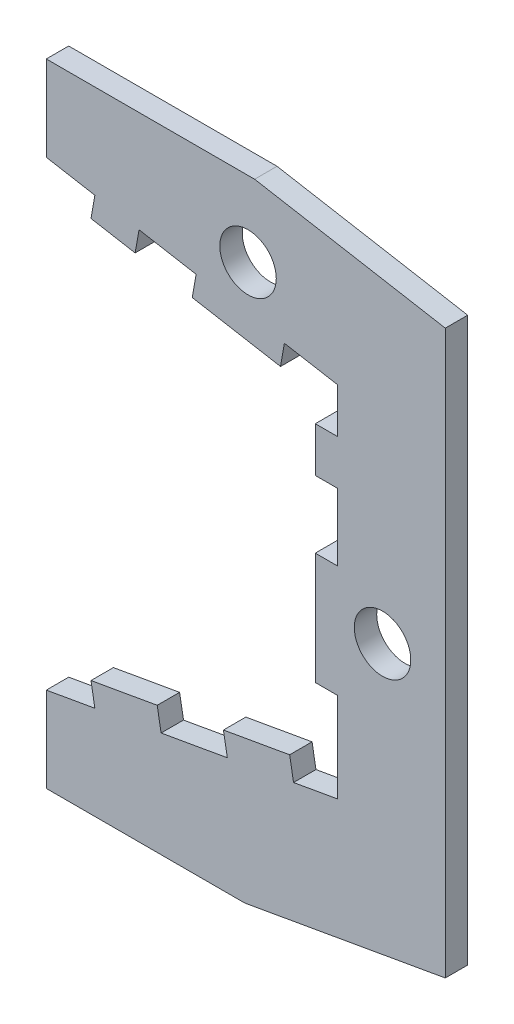
SolidWorks part; units mm, degrees
material "Balsa"
ref_plane "Plan de face" through (0, 0, 0) normal (0, 0, 1) x (1, 0, 0)
ref_plane "Plan de dessus" through (0, 0, 0) normal (0, 1, 0) x (1, 0, 0)
ref_plane "Plan de droite" through (0, 0, 0) normal (1, 0, 0) x (0, 0, -1)
sketch "Esquisse1" plane through (0, 0, 0) normal (0, 0, 1) x (1, 0, 0)
  line L0 (-65, 51.4613) -> (0, 40)
  line L1 (0, 40) -> (0, -40)
  line L2 (-65, -51.4613) -> (0, -40)
  line L3 (-18.4444, 71.4613) -> (-65, 71.4613)
  line L4 (-65, -51.4613) -> (-65, -71.4613)
  line L5 (-20.6259, -71.4613) -> (25, -63.4162)
  line L6 (25, -63.4162) -> (25, 63.8008)
  line L7 (25, 63.8008) -> (-18.4444, 71.4613)
  line L8 (-65, 71.4613) -> (-65, 51.4613)
  line L9 (-18.4444, 71.4613) -> (-20, 53.6808) construction
  line L10 (-65, -71.4613) -> (-20.6259, -71.4613)
  line L11 (0, 0) -> (-84.8855, 0) construction
  circle A0 centre (-20, 53.6808) radius 6.3
  circle A1 centre (10, -5) radius 6.3
  point P4 (-30.4766, 71.4613)
  point P13 (-6.595, 69.3719)
  point P15 (-65, -71.4613)
  dimension "D1" = 12.6
  dimension "D13" = 12.6
  dimension "D2" = 10
  dimension "D3" = 20
  dimension "D4" = 80
  dimension "D5" = 65
  dimension "D6" = 100
  dimension "D7" = 100
  dimension "D8" = 20
  dimension "D9" = 27.4016
  dimension "D10" = 90
  dimension "D11" = 10
  dimension "D12" = 35
  dimension "D14" = 100
extrude "Boss.-Extru.1" add sketch "Esquisse1" along normal blind 5
sketch "Esquisse4" plane through (0, 0, 5) normal (0, 0, 1) x (1, 0, 0)
  line L0 (0, 40) -> (0, -40) construction
  line L1 (0, 5) -> (-5, 5)
  line L2 (0, 5) -> (0, -20)
  line L3 (0, -20) -> (-5, -20)
  line L4 (-5, 5) -> (-5, -20)
  line L5 (-11.8884, 42.0962) -> (-31.5846, 45.5692)
  line L6 (-11.8884, 42.0962) -> (-12.7566, 37.1722)
  line L7 (-31.5846, 45.5692) -> (-32.4528, 40.6452)
  line L8 (-12.7566, 37.1722) -> (-32.4528, 40.6452)
  line L9 (-65, 51.4613) -> (0, 40) construction
  line L10 (-9.8481, -41.7365) -> (-24.6202, -44.3412)
  line L11 (0, 30) -> (-5, 30)
  line L12 (0, 30) -> (0, 20)
  line L13 (0, 20) -> (-5, 20)
  line L14 (-5, 30) -> (-5, 20)
  line L15 (-9.8481, -41.7365) -> (-10.7163, -36.8124)
  line L16 (-24.6202, -44.3412) -> (-25.4884, -39.4172)
  line L17 (-10.7163, -36.8124) -> (-25.4884, -39.4172)
  line L18 (0, -40) -> (-65, -51.4613) construction
  line L19 (-54.1644, -49.5506) -> (-39.3923, -46.9459)
  line L20 (-54.1644, -49.5506) -> (-55.0327, -44.6266)
  line L21 (-39.3923, -46.9459) -> (-40.2606, -42.0219)
  line L22 (-55.0327, -44.6266) -> (-40.2606, -42.0219)
  line L23 (-44.3163, 47.8142) -> (-54.1644, 49.5506)
  line L24 (-44.3163, 47.8142) -> (-45.1846, 42.8901)
  line L25 (-54.1644, 49.5506) -> (-55.0327, 44.6266)
  line L26 (-45.1846, 42.8901) -> (-55.0327, 44.6266)
  circle A0 centre (10, -5) radius 6.3 construction
  circle A1 centre (-20, 53.6808) radius 6.3 construction
  dimension "D1" = 10
  dimension "D2" = 25
  dimension "D3" = 10
  dimension "D4" = 20
  dimension "D5" = 5
  dimension "D6" = 5
  dimension "D7" = 15
  dimension "D8" = 10
  dimension "D9" = 10
  dimension "D10" = 15
  dimension "D11" = 15
  dimension "D12" = 15
  dimension "D13" = 5
  dimension "D14" = 55
  dimension "D15" = 10
extrude "Boss.-Extru.2" add sketch "Esquisse4" against normal blind 5
sketch "Esquisse5" plane through (0, 0, 5) normal (0, 0, 1) x (1, 0, 0)
  line L0 (-65, 70.4613) -> (-18.5319, 70.4613)
  line L1 (-65, 71.4613) -> (-65, 51.4613) construction
  line L2 (-18.5319, 70.4613) -> (24, 62.9617)
  line L3 (24, 62.9617) -> (24, -62.5771)
  line L4 (24, -62.5771) -> (-20.7134, -70.4613)
  line L5 (-20.7134, -70.4613) -> (-65, -70.4613)
  line L6 (-65, -51.4613) -> (-65, -71.4613) construction
  line L7 (-65, -70.4613) -> (-65, -77.1482)
  line L8 (-65, -77.1482) -> (34.4232, -77.1482)
  line L9 (34.4232, -77.1482) -> (34.4232, 88.8936)
  line L10 (34.4232, 88.8936) -> (-65, 88.8936)
  line L11 (-65, 88.8936) -> (-65, 70.4613)
  line L12 (-18.4444, 71.4613) -> (-65, 71.4613) construction
  line L13 (25, 63.8008) -> (-18.4444, 71.4613) construction
  line L14 (25, -63.4162) -> (25, 63.8008) construction
  line L15 (-20.6259, -71.4613) -> (25, -63.4162) construction
  line L16 (-65, -71.4613) -> (-20.6259, -71.4613) construction
  dimension "D1" = 1
  dimension "D2" = 1
  dimension "D3" = 1
  dimension "D4" = 1
  dimension "D5" = 1
extrude "Enlèv. mat.-Extru.1" cut sketch "Esquisse5" against normal blind 5
